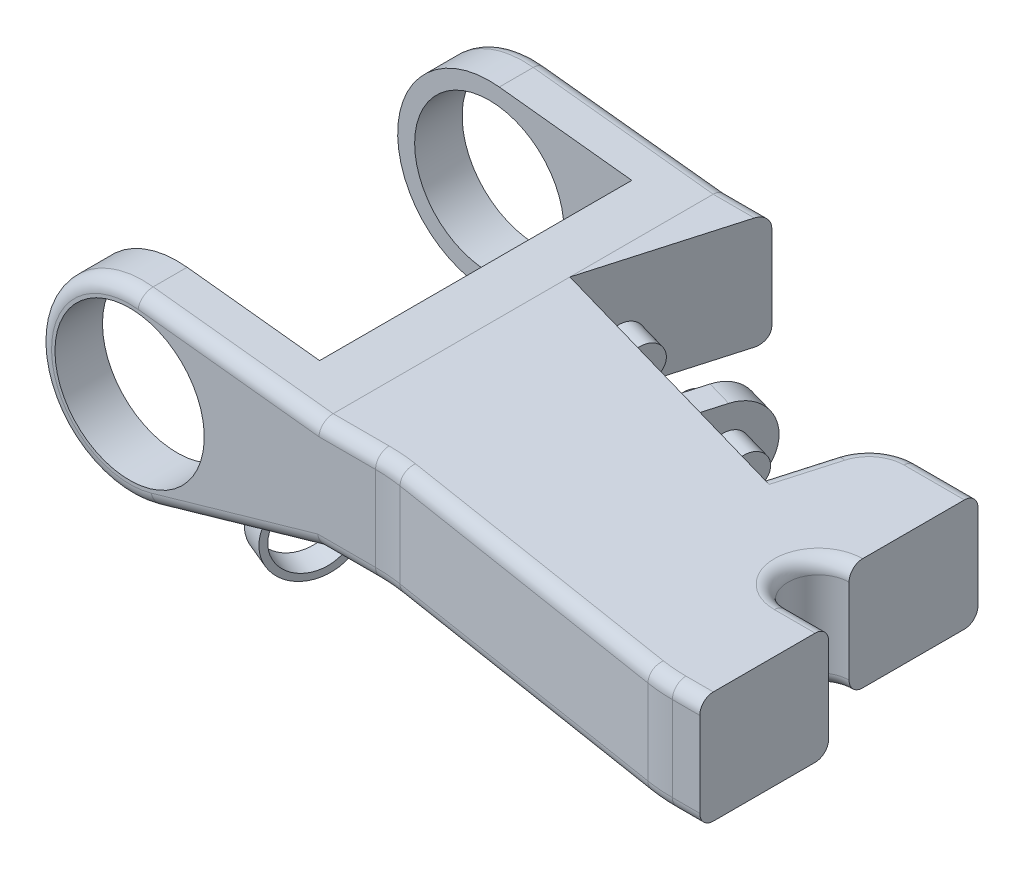
SolidWorks part; units mm, degrees
ref_plane "Спереди" through (0, 0, 0) normal (0, 0, 1) x (1, 0, 0)
ref_plane "Сверху" through (0, 0, 0) normal (0, 1, 0) x (1, 0, 0)
ref_plane "Справа" through (0, 0, 0) normal (1, 0, 0) x (0, 0, -1)
sketch "Эскиз8" plane through (0, 0, 0) normal (0, 1, 0) x (1, 0, 0)
  line L0 (-31.6673, 77.5) -> (-62.0836, 77.5) construction
  line L1 (-85, 43.6529) -> (-6, 21) construction
  line L2 (-106, 13.5) -> (-92.5, 13.5)
  line L3 (-92.5, 13.5) -> (-92.5, 6.5)
  line L4 (-92.5, 6.5) -> (-119.5, 6.5)
  line L6 (-119.5, 6.5) -> (-119.5, 13.5)
  line L7 (-119.5, 13.5) -> (-106, 13.5)
  line L8 (-117, 28.0456) -> (-95, 28.0456) construction
  line L31 (-92.5, 61.5) -> (-119.5, 61.5)
  line L32 (-119.5, 61.5) -> (-119.5, 54.5)
  line L33 (-119.5, 54.5) -> (-92.5, 54.5)
  line L34 (-92.5, 54.5) -> (-92.5, 61.5)
  line L37 (-62.0836, 77.5) -> (-62.0836, 61.5) construction
  line L38 (-62.0836, 61.5) -> (-92.5, 61.5) construction
  line L39 (-11.6673, -9.5) -> (-52.0836, -9.5) construction
  line L44 (-52.0836, -9.5) -> (-52.0836, 6.5) construction
  line L45 (-42.6378, 23.1833) -> (-38.3121, 21.943)
  line L46 (-17.6673, 16.0231) -> (-17.6673, 18.5) construction
  line L47 (-52.0836, 6.5) -> (-92.5, 6.5) construction
  line L48 (-106, 28.0456) -> (-85, 28.0456) construction
  line L52 (-92.5, 54.5) -> (-85, 54.5)
  line L53 (-85, 54.5) -> (-85, 13.5)
  line L54 (-85, 13.5) -> (-92.5, 13.5)
  line L56 (-6, 21) -> (-6, 28) construction
  line L59 (-78, 61.5) -> (-78, 63.0226)
  line L60 (-35.418, 32.0362) -> (-39.7436, 33.2766)
  line L61 (-78, 61.5) -> (-78, 33.3233)
  line L64 (-11.6673, 9.5) -> (-17.6673, 9.5)
  line L65 (-17.6673, 37.5) -> (-17.6673, 18.5) construction
  line L67 (-38.3121, 21.943) -> (-35.418, 32.0362)
  line L68 (-41.1218, 28.4703) -> (-42.6378, 23.1833) construction
  line L69 (-60.3189, 28.2533) -> (-57.4247, 38.3465) construction
  line L70 (-39.7436, 33.2766) -> (-41.1218, 28.4703)
  line L71 (-41.1218, 28.4703) -> (-36.7961, 27.2299)
  line L72 (-42.6378, 23.1833) -> (-78, 33.3233)
  line L79 (-38.3121, 21.943) -> (-17.6673, 16.0231) construction
  line L82 (-35.418, 32.0362) -> (-33.8512, 37.5) construction
  line L83 (-57.665, 38.4155) -> (-61.5101, 39.518)
  line L84 (-57.4247, 38.3465) -> (-57.665, 38.4155)
  line L85 (-57.4247, 38.3465) -> (-57.1844, 38.2776)
  line L86 (-57.1844, 38.2776) -> (-60.0786, 28.1844)
  line L87 (-61.5101, 39.518) -> (-62.8883, 34.7117)
  line L88 (-62.8883, 34.7117) -> (-58.5626, 33.4713)
  line L89 (-57.1844, 38.2776) -> (-53.3394, 37.1751)
  line L90 (-53.3394, 37.1751) -> (-56.2335, 27.0818)
  line L91 (-62.8883, 34.7117) -> (-64.4043, 29.4248) construction
  line L92 (-33.8512, 37.5) -> (-17.6673, 37.5) construction
  circle A1 centre (-106, 28.0456) radius 11
  circle A6 centre (-106, 28.0456) radius 13.5
  arc A8 (-17.6673, 18.5) -> (-17.6673, 9.5) centre (-17.6673, 14) ccw
  spline S0 degree 3 poles (-31.6673, 77.5) (-62.0836, 77.5) (-62.0836, 61.5) (-92.5, 61.5) knots 0 0 0 0 1 1 1 1
  spline S1 degree 3 poles (-11.6673, -9.5) (-52.0836, -9.5) (-52.0836, 6.5) (-92.5, 6.5) knots 0 0 0 0 1 1 1 1
  spline S3 degree 2 poles (-35.418, 32.0362) (-33.8512, 37.5) (-17.6673, 37.5) knots 0 0 0 1 1 1
  point P48 (-60.3189, 28.2533)
sketch "Эскиз10" plane through (0, 0, 0) normal (0, 1, 0) x (1, 0, 0)
  line L0 (-34.4146, 72.312) -> (-60.5171, 61.5) construction
  line L5 (-20.4853, 37.5) -> (-20.4853, 18.5)
  line L9 (-14.4853, 9.5) -> (-14.4853, -9.5)
  line L11 (-20.4853, -9.5) -> (-14.4853, -9.5)
  line L14 (-85, 51) -> (-85, 13.5)
  line L22 (-14.4853, 9.5) -> (-20.4853, 9.5)
  line L23 (-20.4853, 9.5) -> (-20.4853, 18.5) construction
  line L31 (-20.4853, 9.5) -> (-20.4853, -9.5) construction
  line L35 (-119.5, 58) -> (-119.5, 54.5)
  line L46 (-29.3807, 37.5) -> (-20.4853, 37.5)
  line L47 (-15.6546, 17.0065) -> (-85, 36.8909) construction
  line L52 (-38.7777, 23.6369) -> (-36.297, 32.2883)
  line L60 (-78, 34.8837) -> (-60.3114, 29.8116)
  line L61 (-56.4663, 28.709) -> (-38.7777, 23.6369)
  line L62 (-75.5193, 43.5351) -> (-78, 34.8837)
  line L64 (-71.3715, 58) -> (-75.5193, 43.5351)
  line L65 (-56.4663, 28.709) -> (-53.0209, 40.7248)
  line L66 (-53.0209, 40.7248) -> (-56.8659, 41.8274)
  line L67 (-56.8659, 41.8274) -> (-60.3114, 29.8116)
  line L68 (-119.5, -2) -> (-67.7872, -2)
  line L69 (-119.5, 58) -> (-68.9668, 58)
  line L70 (-60.5171, 61.5) -> (-68.9668, 58)
  line L71 (-119.5, -2) -> (-119.5, 5)
  line L72 (-119.5, 5) -> (-85, 5)
  line L73 (-85, 13.5) -> (-85, 5)
  line L74 (-119.5, 58) -> (-119.5, 51)
  line L75 (-119.5, 51) -> (-85, 51)
  line L76 (-68.9668, 58) -> (-67.7872, -2) construction
  line L77 (-67.7872, -2) -> (-20.4853, -9.5)
  arc A0 (-20.4853, 18.5) -> (-20.4853, 9.5) centre (-20.4853, 14) ccw
  arc A8 (-36.297, 32.2883) -> (-29.3807, 37.5) centre (-29.3807, 30.3051) cw
  arc A9 (-20.4853, 37.5) -> (-38.7777, 23.6369) centre (-20.4853, 18.5) ccw construction
extrude "Бобышка-Вытянуть1" add sketch "Эскиз10" along normal mid plane 27 separate body
sketch "Эскиз11" plane through (0, 0, 0) normal (0, 0, 1) x (1, 0, 0)
  line L10 (-11.6673, -6) -> (-11.6673, 10.5)
  line L16 (-106, 0) -> (-11.6673, 0) construction
  line L31 (-11.6673, 10.5) -> (-78, 10.5)
  line L50 (-119.5, 13.5) -> (-11.6673, 13.5)
  line L51 (-119.5, 13.5) -> (-119.5, -13.5)
  line L52 (-119.5, -13.5) -> (-11.6673, -13.5)
  line L53 (-11.6673, 13.5) -> (-11.6673, -13.5)
  line L55 (-78, 10.5) -> (-78, -6)
  line L56 (-78, -6) -> (-11.6673, -6)
  line L57 (-78, -6) -> (-102.2714, -12.9749)
  line L58 (-78, 10.5) -> (-104.5232, 13.419)
  circle A2 centre (-106, 0) radius 11
  circle A5 centre (-106, 0) radius 13.5
extrude "Вырез-Вытянуть1" cut sketch "Эскиз11" against normal through all both and the other way through all
sketch "Эскиз12" plane through (-63.628, 0, -18.245) normal (-0.9613, 0, -0.2756) x (-0.2756, 0, 0.9613)
  line L0 (-18.5327, 0) -> (-18.5327, -6) construction
  line L1 (-21.0327, 0) -> (-18.5327, 0) construction
  circle A0 centre (-18.5327, 0) radius 2.5
extrude "Бобышка-Вытянуть2" add sketch "Эскиз12" along normal blind 4.5
sketch "Эскиз13" plane through (-42.0943, 0, -12.0704) normal (-0.9613, 0, -0.2756) x (-0.2756, 0, 0.9613)
  line L0 (-21.0327, 0) -> (-18.5327, 0) construction
  line L2 (-18.5327, 0) -> (-18.5327, -6) construction
  circle A0 centre (-18.5327, 0) radius 2.5
extrude "Бобышка-Вытянуть3" add sketch "Эскиз13" along normal blind 4.5
fillet "Скругление1" radius 25 2 edges at (-20.4853, 2.25, 9.5) (-67.7872, 2.25, 2)
sketch "Эскиз21" plane through (-81.3167, 0, -23.3172) normal (0.9613, 0, 0.2756) x (0.2756, 0, -0.9613)
  line L0 (12.0327, -6) -> (18.5327, -6)
  line L1 (12.0327, -6) -> (36.0805, -6) construction
  line L2 (18.5327, -6) -> (18.5327, 0)
  circle A0 centre (18.5327, 0) radius 2.5
extrude "Бобышка-Вытянуть5" add sketch "Эскиз21" along normal blind 4.5
sketch "Эскиз22" plane through (-59.783, 0, -17.1425) normal (0.9613, 0, 0.2756) x (0.2756, 0, -0.9613)
  line L0 (12.0327, -6) -> (18.5327, -6)
  line L2 (18.5327, -6) -> (18.5327, 0)
  circle A0 centre (18.5327, 0) radius 2.5
extrude "Бобышка-Вытянуть6" add sketch "Эскиз22" along normal blind 4.5
sketch "Эскиз24" plane through (-59.783, 0, -17.1425) normal (0.9613, 0, 0.2756) x (0.2756, 0, -0.9613)
  line L0 (18.5327, -6) -> (24.5327, -6)
  line L1 (24.5327, -6) -> (24.5327, 0)
  line L2 (24.5327, 0) -> (24.5327, 10.5)
  line L3 (24.5327, 10.5) -> (12.0327, 10.5)
  line L5 (18.5327, 6) -> (12.0327, 6)
  line L6 (12.0327, 10.5) -> (12.0327, 6)
  circle A0 centre (18.5327, 0) radius 6
  line M2 (12.0327, -6) -> (24.5327, -6)
  line M3 (24.5327, -6) -> (24.5327, 10.5)
  line M4 (24.5327, 10.5) -> (12.0327, 10.5)
  line M5 (12.0327, 10.5) -> (12.0327, -6)
extrude "Вырез-Вытянуть5" cut sketch "Эскиз24" against normal blind 4 contours A0 L5 M3 M4 M5 | A0 M2 M3
fillet "Скругление6" radius 2 28 edges at (-37.5373, -6, -27.9626) (-33.7108, -6, -36.0512) (-37.5373, 10.5, -27.9626) (-33.7108, 10.5, -36.0512) (-17.4853, -6, -9.5) (-17.4853, 10.5, -9.5) (-24.933, -6, -37.5) (-24.933, 10.5, -37.5) (-16.5005, -6, 9.5) (-16.5005, 10.5, 9.5) (-24.9853, -6, -14) (-24.9853, 10.5, -14) (-73.8784, -6, 2) (-73.8784, 10.5, 2) (-91.2616, 11.9595, -58) (-119.4511, -1.1476, -58) (-90.1357, -9.4874, 2) (-119.4511, -1.1476, 2) (-90.1357, -9.4874, -58) (-74.6858, -6, -58) (-74.6858, 10.5, -58) (-91.2616, 11.9595, 2) (-67.7933, -6, 2.0772) (-44.1362, -6, 5.75) (-20.4792, -6, 9.4228) (-67.7933, 10.5, 2.0772) (-44.1362, 10.5, 5.75) (-20.4792, 10.5, 9.4228)
ref_plane "Плоскость1" through (-79.8495, 0, -33.0748) normal (-0.9239, 0, -0.3827) x (-0.3827, 0, 0.9239)
sketch "Эскиз25" plane through (-79.8495, 0, -33.0748) normal (-0.9239, 0, -0.3827) x (-0.3827, 0, 0.9239)
  circle A0 centre (27.9359, -12) radius 5
  circle A1 centre (27.9359, -12) radius 6
extrude "Бобышка-Вытянуть7" add sketch "Эскиз25" against normal blind 4
